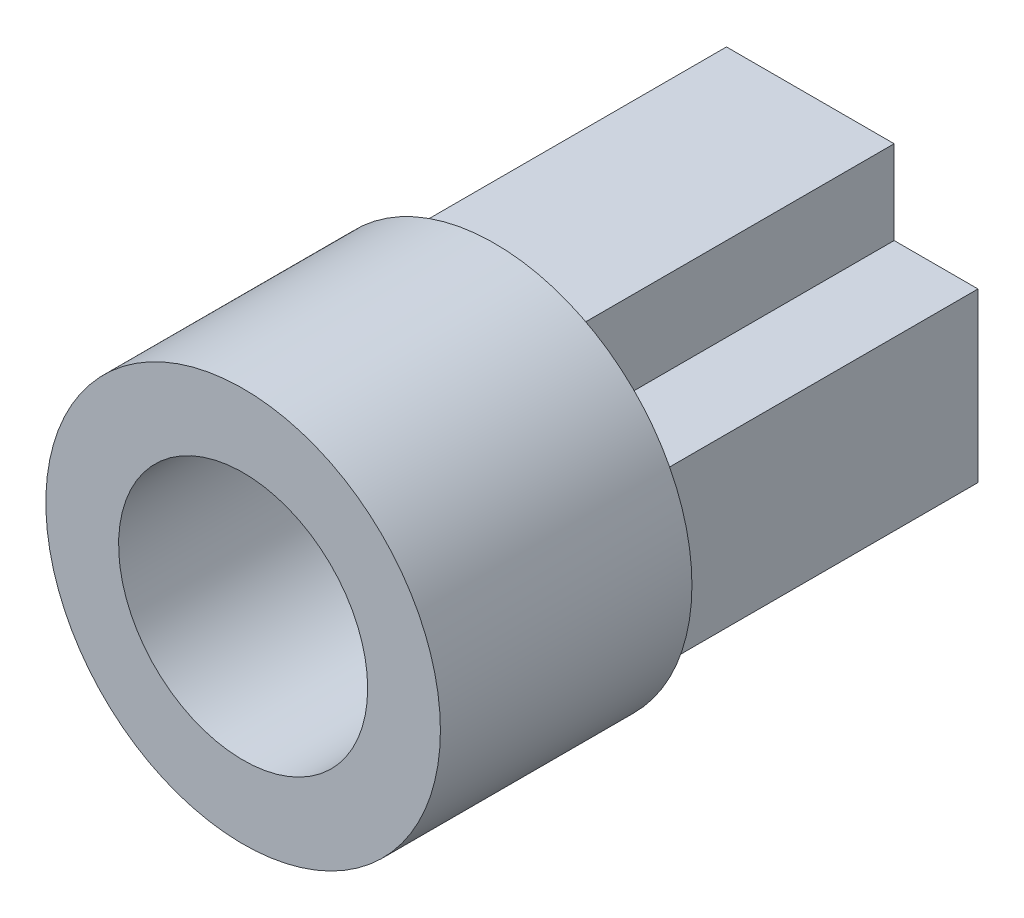
SolidWorks part; units mm, degrees
ref_plane "Front Plane" through (0, 0, 0) normal (0, 0, 1) x (1, 0, 0)
ref_plane "Top Plane" through (0, 0, 0) normal (0, 1, 0) x (1, 0, 0)
ref_plane "Right Plane" through (0, 0, 0) normal (1, 0, 0) x (0, 0, -1)
sketch "Sketch1" plane through (0, 0, 0) normal (0, 0, 1) x (1, 0, 0)
  circle A0 centre (0, 0) radius 4
  circle A1 centre (0, 0) radius 2.525
  dimension "D1" = 8
  dimension "D2" = 5.05
extrude "Boss-Extrude1" add sketch "Sketch1" along normal blind 5.1
sketch "Sketch2" plane through (0, 0, 0) normal (0, 0, -1) x (-1, 0, 0)
  line L0 (-1.7, 3.4) -> (-1.7, 1.7)
  line L1 (-1.7, 1.7) -> (-3.4, 1.7)
  line L2 (-3.4, 1.7) -> (-3.4, -1.7)
  line L3 (-3.4, -1.7) -> (-1.7, -1.7)
  line L4 (-1.7, -1.7) -> (-1.7, -3.4)
  line L5 (-1.7, -3.4) -> (1.7, -3.4)
  line L6 (1.7, -3.4) -> (1.7, -1.7)
  line L7 (1.7, -1.7) -> (3.4, -1.7)
  line L8 (3.4, -1.7) -> (3.4, 1.7)
  line L9 (3.4, 1.7) -> (1.7, 1.7)
  line L10 (1.7, 1.7) -> (1.7, 3.4)
  line L11 (1.7, 3.4) -> (-1.7, 3.4)
  line L12 (-1.05, 2.45) -> (-1.05, 1.55)
  line L13 (-1.55, 1.05) -> (-2.45, 1.05)
  line L14 (-2.45, 1.05) -> (-2.45, -1.05)
  line L15 (-2.45, -1.05) -> (-1.55, -1.05)
  line L16 (-1.05, -1.55) -> (-1.05, -2.45)
  line L17 (-1.05, -2.45) -> (1.05, -2.45)
  line L18 (1.05, -2.45) -> (1.05, -1.55)
  line L19 (1.55, -1.05) -> (2.45, -1.05)
  line L20 (2.45, -1.05) -> (2.45, 1.05)
  line L21 (2.45, 1.05) -> (1.55, 1.05)
  line L22 (1.05, 1.55) -> (1.05, 2.45)
  line L23 (1.05, 2.45) -> (-1.05, 2.45)
  arc A0 (-1.55, -1.05) -> (-1.05, -1.55) centre (-1.55, -1.55) cw
  arc A1 (-1.05, 1.55) -> (-1.55, 1.05) centre (-1.55, 1.55) cw
  arc A2 (1.55, 1.05) -> (1.05, 1.55) centre (1.55, 1.55) cw
  arc A3 (1.05, -1.55) -> (1.55, -1.05) centre (1.55, -1.55) cw
  point P2 (0, -3.4)
  point P31 (-1.05, 1.05)
  point P34 (1.05, 1.05)
  dimension "D24" = 0.5
  dimension "D25" = 0.5
  dimension "D26" = 0.5
  dimension "D27" = 0.5
  dimension "D1" = 3.4
  dimension "D2" = 1.7
  dimension "D3" = 3.4
  dimension "D4" = 1.7
  dimension "D5" = 1.7
  dimension "D6" = 3.4
  dimension "D7" = 1.7
  dimension "D8" = 1.7
  dimension "D9" = 3.4
  dimension "D10" = 1.7
  dimension "D11" = 3.4
  dimension "D12" = 3.4
  dimension "D13" = 2.45
  dimension "D14" = 2.45
  dimension "D15" = 1.05
  dimension "D16" = 1.05
  dimension "D17" = 2.45
  dimension "D18" = 1.05
  dimension "D19" = 1.05
  dimension "D20" = 1.05
  dimension "D21" = 1.05
  dimension "D22" = 1.05
  dimension "D23" = 2.45
extrude "Boss-Extrude2" add sketch "Sketch2" along normal blind 6.4
sketch "Sketch3" plane through (0, 0, 0) normal (0, 0, -1) x (-1, 0, 0)
  line L0 (-0.8074, 2.1512) -> (-0.8074, 0.8344)
  line L1 (-0.8074, 0.8344) -> (-2.1967, 0.8344)
  line L2 (-2.1967, 0.8344) -> (-2.1967, -0.7965)
  line L3 (-2.1967, -0.7965) -> (-0.8074, -0.7965)
  line L4 (-0.8074, -0.7965) -> (-0.8074, -2.1858)
  line L5 (-0.8074, -2.1858) -> (0.7873, -2.1858)
  line L6 (0.7873, -2.1858) -> (0.7873, -0.7965)
  line L7 (0.7873, -0.7965) -> (2.1525, -0.7965)
  line L8 (2.1525, -0.7965) -> (2.1525, 0.8344)
  line L9 (2.1525, 0.8344) -> (0.7873, 0.8344)
  line L10 (0.7873, 0.8344) -> (0.7873, 2.1512)
  line L11 (0.7873, 2.1512) -> (-0.8074, 2.1512)
  circle A0 centre (0, 0) radius 2.5
extrude "Boss-Extrude5" add sketch "Sketch3" against normal blind 1.1
